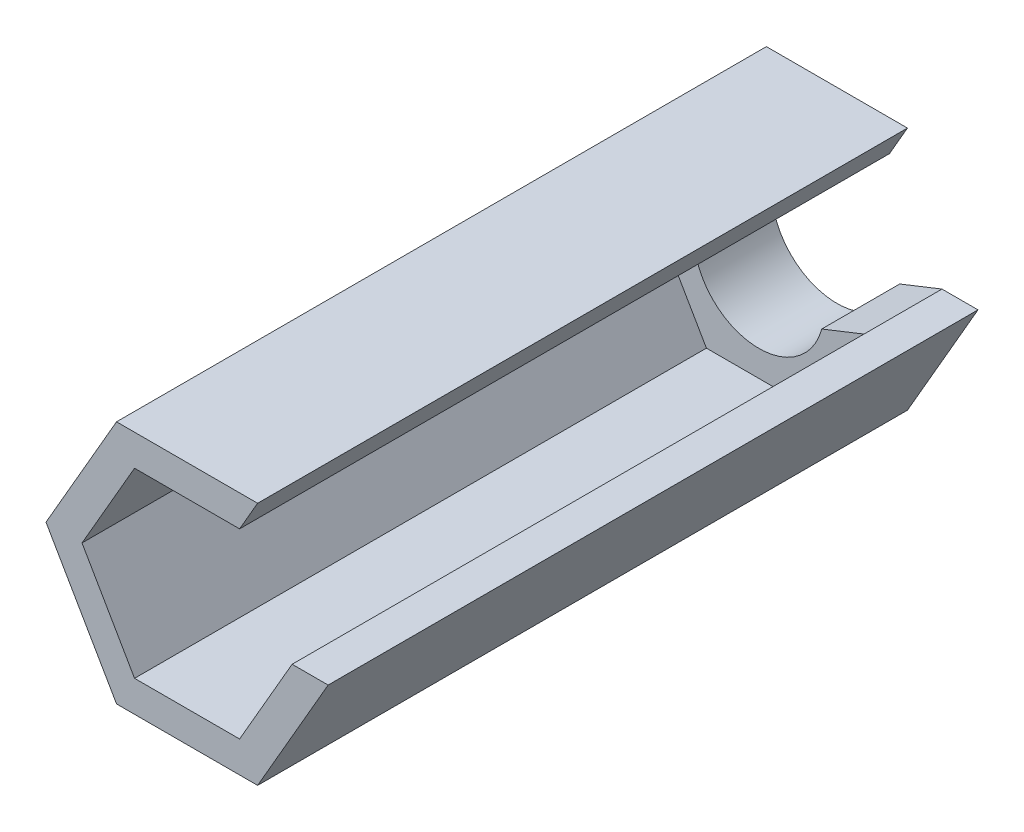
SolidWorks part; units mm, degrees
ref_plane "Front Plane" through (0, 0, 0) normal (0, 0, 1) x (1, 0, 0)
ref_plane "Top Plane" through (0, 0, 0) normal (0, 1, 0) x (1, 0, 0)
ref_plane "Right Plane" through (0, 0, 0) normal (1, 0, 0) x (0, 0, -1)
sketch "Sketch2" plane through (0, 0, 0) normal (0, 0, 1) x (1, 0, 0)
  line L0 (2.5663, 4.445) -> (3.4462, 5.969)
  line L1 (6.8924, 0) -> (3.4462, 5.969) construction
  line L2 (3.4462, 5.969) -> (-3.4462, 5.969)
  line L3 (-3.4462, 5.969) -> (-6.8924, 0)
  line L4 (-6.8924, 0) -> (-3.4462, -5.969)
  line L5 (-3.4462, -5.969) -> (3.4462, -5.969)
  line L6 (3.4462, -5.969) -> (6.8924, 0)
  line L7 (5.1326, 0) -> (2.5663, 4.445) construction
  line L8 (2.5663, 4.445) -> (-2.5663, 4.445)
  line L9 (-2.5663, 4.445) -> (-5.1326, 0)
  line L10 (-5.1326, 0) -> (-2.5663, -4.445)
  line L11 (-2.5663, -4.445) -> (2.5663, -4.445)
  line L12 (2.5663, -4.445) -> (5.1326, 0)
  line L13 (5.1326, 0) -> (6.8924, 0)
  circle A0 centre (0, 0) radius 5.969 construction
  circle A1 centre (0, 0) radius 4.445 construction
  dimension "D1" = 11.938
  dimension "D2" = 8.89
extrude "Boss-Extrude1" add sketch "Sketch2" along normal blind 31.75
sketch "Sketch3" plane through (0, 0, 0) normal (0, 0, -1) x (-1, 0, 0)
  line L0 (-5.1326, 0) -> (-3.0681, -0.817)
  line L1 (5.1326, 0) -> (2.5663, 4.445)
  line L2 (2.5663, 4.445) -> (-2.5663, 4.445)
  line L3 (-2.5663, 4.445) -> (-5.1326, 0) construction
  line L4 (-5.1326, 0) -> (-2.5663, -4.445)
  line L5 (-2.5663, -4.445) -> (2.5663, -4.445)
  line L6 (2.5663, -4.445) -> (5.1326, 0)
  line L7 (-2.5663, 4.445) -> (-0.8265, 3.0655)
  circle A0 centre (0, 0) radius 4.445 construction
  arc A1 (-3.0681, -0.817) -> (-0.8265, 3.0655) centre (0, 0) ccw
  point P1 (11.4701, 6.4592)
  dimension "D1" = 8.89
  dimension "D2" = 6.35
extrude "Boss-Extrude2" add sketch "Sketch3" against normal blind 3.81
